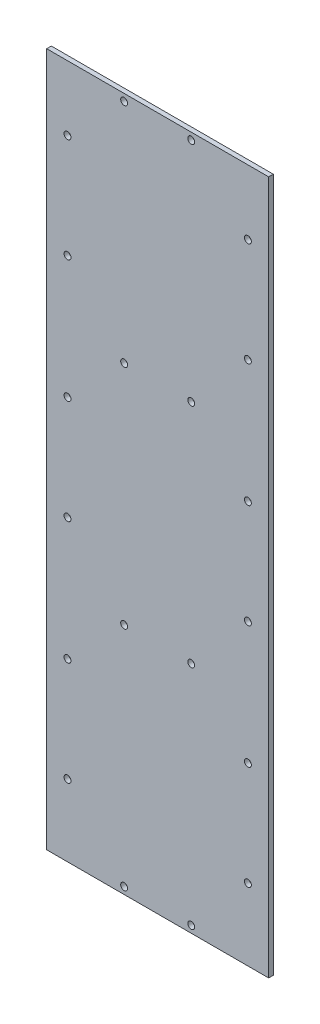
SolidWorks part; units mm, degrees
material "Alumina"
ref_plane "Front Plane" through (0, 0, 0) normal (0, 0, 1) x (1, 0, 0)
ref_plane "Top Plane" through (0, 0, 0) normal (0, 1, 0) x (1, 0, 0)
ref_plane "Right Plane" through (0, 0, 0) normal (1, 0, 0) x (0, 0, -1)
sketch "Sketch1" plane through (0, 0, 0) normal (0, 0, 1) x (1, 0, 0)
  line L1 (48, -150) -> (-48, -150)
  line L2 (48, -150) -> (48, 150)
  line L3 (48, 150) -> (-48, 150)
  line L4 (-48, -150) -> (-48, 150)
  line L5 (48, -150) -> (-48, 150) construction
  line L6 (48, 150) -> (-48, -150) construction
  point P0 (0, 0)
  dimension "D1" = 96
  dimension "D2" = 300
extrude "Boss-Extrude1" add sketch "Sketch1" along normal blind 2
sketch "Sketch2" plane through (0, 0, 2) normal (0, 0, 1) x (1, 0, 0)
  line L0 (-48, 150) -> (-48, -150) construction
  line L1 (48, 150) -> (-48, 150) construction
  line L2 (-48, -150) -> (48, -150) construction
  line L3 (48, -150) -> (48, 150) construction
  line L4 (0, -1.1) -> (0, 1.1) construction
  circle A0 centre (-39, 122) radius 1.5
  circle A1 centre (-39, 77) radius 1.5
  circle A2 centre (39, 122) radius 1.5
  circle A3 centre (39, 77) radius 1.5
  circle A4 centre (-39, 24) radius 1.5
  circle A5 centre (-39, -21) radius 1.5
  circle A6 centre (39, 24) radius 1.5
  circle A7 centre (39, -21) radius 1.5
  circle A8 centre (-39, -74) radius 1.5
  circle A9 centre (-39, -119) radius 1.5
  circle A10 centre (39, -74) radius 1.5
  circle A11 centre (39, -119) radius 1.5
  circle A13 centre (14.5, -147) radius 1.5
  circle A14 centre (-14.5, -147) radius 1.5
  circle A15 centre (-14.5, -49) radius 1.5
  circle A16 centre (14.5, -49) radius 1.5
  circle A17 centre (-14.5, 49) radius 1.5
  circle A18 centre (14.5, 49) radius 1.5
  circle A19 centre (-14.5, 147) radius 1.5
  circle A20 centre (14.5, 147) radius 1.5
  dimension "D1" = 3
  dimension "D3" = 28
  dimension "D4" = 3
  dimension "D6" = 9
  dimension "D10" = 3
  dimension "D11" = 33.5
  dimension "D13" = 3
  dimension "D2" = 9
  dimension "D5" = 45
  dimension "D9" = 31
  dimension "D7" = 2
  dimension "D8" = 3
  dimension "D12" = 4
extrude "Cut-Extrude1" cut sketch "Sketch2" against normal blind 10
